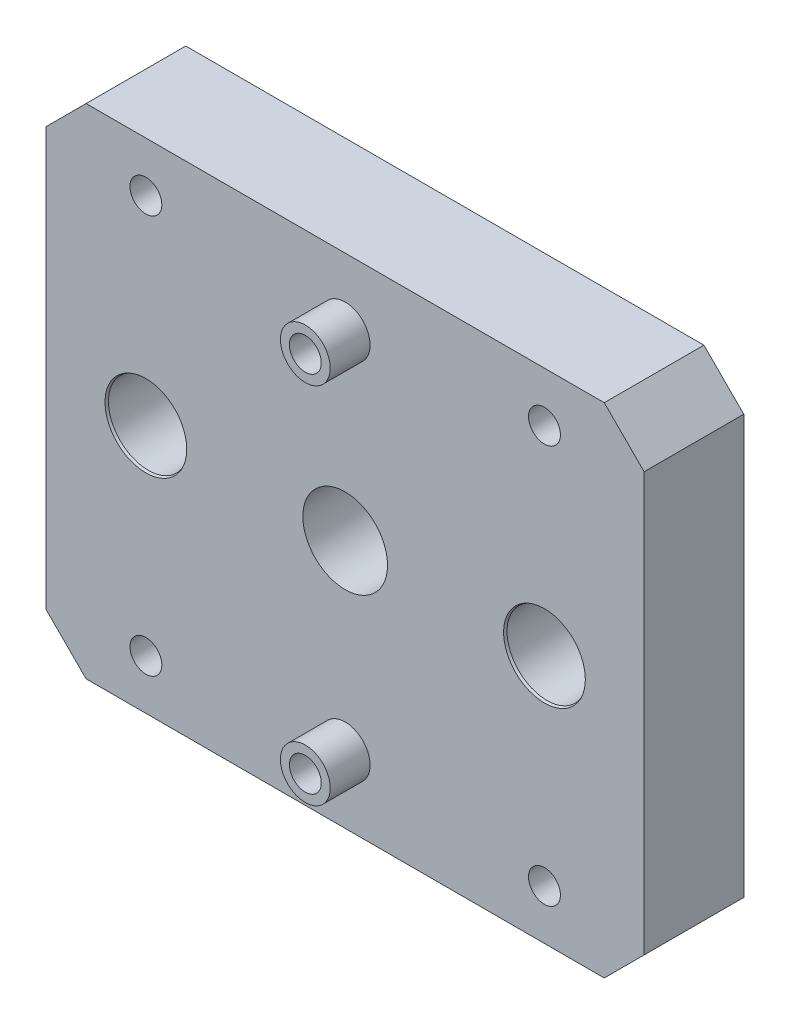
SolidWorks part; units mm, degrees
ref_plane "前视基准面" through (0, 0, 0) normal (0, 0, 1) x (1, 0, 0)
ref_plane "上视基准面" through (0, 0, 0) normal (0, 1, 0) x (1, 0, 0)
ref_plane "右视基准面" through (0, 0, 0) normal (1, 0, 0) x (0, 0, -1)
other "Configuration Table"
sketch "草图1" plane through (0, 0, 0) normal (0, 0, 1) x (1, 0, 0)
  line L1 (-30, -25) -> (30, -25)
  line L2 (-30, -25) -> (-30, 25)
  line L3 (-30, 25) -> (30, 25)
  line L4 (30, -25) -> (30, 25)
  line L5 (-30, -25) -> (30, 25) construction
  line L6 (-30, 25) -> (30, -25) construction
  point P0 (0, 0)
  dimension "D1" = 50
  dimension "D2" = 60
extrude "凸台-拉伸1" add sketch "草图1" along normal blind 10
hole_wizard "孔1" positions "草图2" profile "草图3" legacy
sketch "草图2" plane through (0, 0, 10) normal (0, 0, 1) x (1, 0, 0)
  point P0 (0, 0)
sketch "草图3" plane through (0, 0, 10) normal (1, 0, 0) x (0, -1, 0)
  line L0 (0, 0) -> (0, 20)
  line L1 (0, 20) -> (4.25, 20)
  line L2 (4.25, 20) -> (4.25, 0)
  line L3 (4.25, 0) -> (0, 0)
  line L4 (0, 110) -> (0, -10) construction
  dimension "直径" = 8.5
  dimension "深度" = 20
hole_wizard "孔2" positions "草图4" profile "草图5" legacy end condition through all
sketch "草图4" plane through (0, 0, 10) normal (0, 0, 1) x (1, 0, 0)
  point P0 (20, 0)
  point P2 (-20, 0)
  dimension "D1" = 20
  dimension "D2" = 20
sketch "草图5" plane through (20, 0, 10) normal (1, 0, 0) x (0, -1, 0)
  line L0 (0, 0) -> (0, 10)
  line L1 (0, 10) -> (4, 10)
  line L2 (4, 10) -> (4, 0.2414)
  line L3 (4, 0.2414) -> (4.1, 0)
  line L4 (4.1, 0) -> (0, 0)
  line L5 (0, -6.4453) -> (0, 115.525) construction
  line L6 (-4, 0.2414) -> (-4.1, 0) construction
  dimension "直径" = 8
  dimension "深度" = 10
  dimension "锥坑角度" = 45
  dimension "锥坑直径" = 8.2
sketch "草图9" plane through (0, 0, 10) normal (0, 0, 1) x (1, 0, 0)
  circle A0 centre (0, 18.25) radius 2.5
  circle A1 centre (0, -18.25) radius 2.5
  dimension "D1" = 5
  dimension "D2" = 5
  dimension "D3" = 18.25
  dimension "D4" = 18.25
extrude "凸台-拉伸3" add sketch "草图9" along normal blind 4
hole_wizard "孔3" positions "草图10" profile "草图11" legacy end condition through all
sketch "草图10" plane through (0, 0, 14) normal (0, 0, 1) x (1, 0, 0)
  point P0 (0, 18.25)
  point P3 (0, -18.25)
sketch "草图11" plane through (0, 18.25, 14) normal (1, 0, 0) x (0, -1, 0)
  line L0 (0, 0) -> (0, 14)
  line L1 (0, 14) -> (1.6, 14)
  line L2 (1.6, 14) -> (1.6, 0)
  line L3 (1.6, 0) -> (0, 0)
  line L4 (0, 110) -> (0, -10) construction
  dimension "直径" = 3.2
  dimension "深度" = 14
sketch "草图15" plane through (0, 0, 10) normal (0, 0, 1) x (1, 0, 0)
  line L0 (-30, 0) -> (30, 0)
  line L1 (-30, 25) -> (-30, -25) construction
  line L2 (30, -25) -> (30, 25) construction
  line L3 (0, 25) -> (0, -25)
  line L4 (30, 25) -> (-30, 25) construction
  line L5 (-30, -25) -> (30, -25) construction
  line L6 (0, 0) -> (-29.5019, 29.5019)
  line L8 (30, 14.0027) -> (14.0027, 14.0027)
  line L9 (-30, 25) -> (-14.0027, 25)
  line L10 (-30, 25) -> (-30, 14.0027)
  line L11 (-30, 14.0027) -> (-14.0027, 14.0027)
  line L12 (-14.0027, 25) -> (-14.0027, 14.0027)
  line L13 (14.0027, 25) -> (14.0027, 14.0027)
  line L14 (30, 25) -> (14.0027, 25)
  line L15 (30, 25) -> (30, 14.0027)
  line L16 (-30, -14.0027) -> (-14.0027, -14.0027)
  line L17 (-14.0027, -25) -> (-14.0027, -14.0027)
  line L18 (-30, -25) -> (-14.0027, -25)
  line L19 (-30, -25) -> (-30, -14.0027)
  line L20 (30, -25) -> (30, -14.0027)
  line L21 (30, -25) -> (14.0027, -25)
  line L22 (14.0027, -25) -> (14.0027, -14.0027)
  line L23 (30, -14.0027) -> (14.0027, -14.0027)
  circle A0 centre (-20, 20) radius 1.6
  circle A1 centre (20, 20) radius 1.6
  circle A2 centre (20, -20) radius 1.6
  circle A3 centre (-20, -20) radius 1.6
  dimension "D3" = 3.2
  dimension "D1" = 45
  dimension "D2" = 40
chamfer "倒角1" distance 4 angle 45 4 edges at (30, -25, 5) (-30, -25, 5) (-30, 25, 5) (30, 25, 5)
extrude "切除-拉伸1" cut sketch "草图15" against normal through all contours L6 A0 | L6 A0 | A1 | A2 | A3
